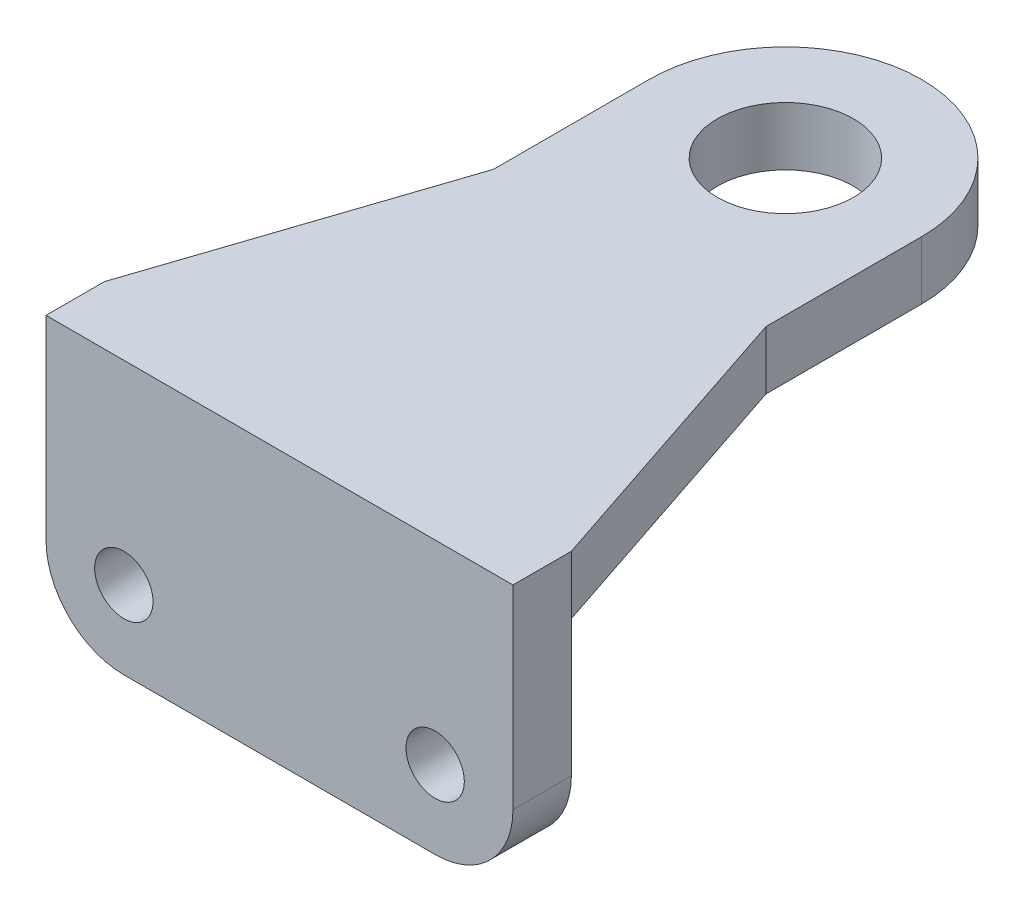
SolidWorks part; units mm, degrees
ref_plane "Ön Düzlem" through (0, 0, 0) normal (0, 0, 1) x (1, 0, 0)
ref_plane "Üst Düzlem" through (0, 0, 0) normal (0, 1, 0) x (1, 0, 0)
ref_plane "Sağ Düzlem" through (0, 0, 0) normal (1, 0, 0) x (0, 0, -1)
sketch "Çizim1" plane through (0, 0, 0) normal (0, 0, 1) x (1, 0, 0)
  line L1 (-142.0565, 60.1774) -> (-22.0565, 60.1774)
  line L2 (-142.0565, 60.1774) -> (-142.0565, 10.1774)
  line L3 (-122.0565, -9.8226) -> (-42.0565, -9.8226)
  line L4 (-22.0565, 60.1774) -> (-22.0565, 10.1774)
  arc A0 (-142.0565, 10.1774) -> (-122.0565, -9.8226) centre (-122.0565, 10.1774) ccw
  arc A1 (-42.0565, -9.8226) -> (-22.0565, 10.1774) centre (-42.0565, 10.1774) ccw
  circle A2 centre (-122.0565, 10.1774) radius 7.5
  circle A3 centre (-42.0565, 10.1774) radius 7.5
  point P0 (-82.0565, 25.1774)
  point P7 (-142.0565, -9.8226)
  point P10 (-22.0565, -9.8226)
  dimension "D3" = 20
  dimension "D4" = 15
  dimension "D5" = 15
  dimension "D1" = 70
  dimension "D2" = 120
extrude "Yükseklik-Ekstrüzyon1" add sketch "Çizim1" along normal blind 15
sketch "Çizim2" plane through (0, 60.1774, 0) normal (0, 1, 0) x (1, 0, 0)
  line L0 (-117.0565, 115) -> (-117.0565, 75)
  line L1 (-117.0565, 75) -> (-142.0565, 0)
  line L2 (-22.0565, 0) -> (-142.0565, 0) construction
  line L3 (-47.0565, 115) -> (-47.0565, 75)
  line L4 (-47.0565, 75) -> (-22.0565, 0)
  line L5 (-142.0565, 0) -> (-22.0565, 0)
  arc A0 (-47.0565, 115) -> (-117.0565, 115) centre (-82.0565, 115) ccw
  circle A1 centre (-82.0565, 115) radius 17.5
  dimension "D1" = 70
  dimension "D2" = 35
  dimension "D3" = 75
  dimension "D4" = 75
  dimension "D5" = 115
  dimension "D6" = 25
  dimension "D7" = 25
extrude "Yükseklik-Ekstrüzyon2" add sketch "Çizim2" against normal blind 15
ref_plane "Düzlem1" through (-82.0565, 0, 0) normal (-1, 0, 0) x (0, 0, 1)
sketch "Çizim4" plane through (-82.0565, 0, 0) normal (-1, 0, 0) x (0, 0, 1)
  line L0 (0, -4.8226) -> (-50, 45.1774)
  line L1 (-75, 45.1774) -> (0, 45.1774) construction
  line L3 (15, -9.8226) -> (0, -9.8226) construction
  dimension "D1" = 5
  dimension "D2" = 50
rib "Feder1" sketch "Çizim4" sketch "Çizim4" thickness 10 extrusion direction parallel to sketch draft on no parameters "D1"=10
